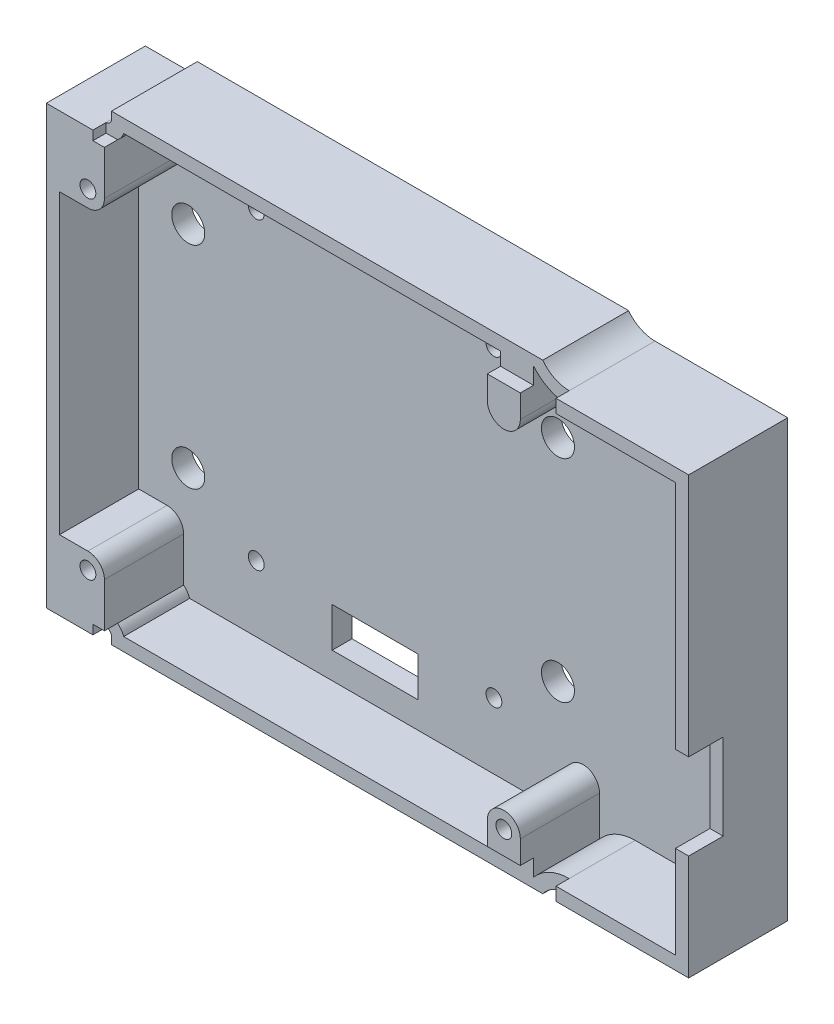
SolidWorks part; units mm, degrees
ref_plane "Ebene vorne" through (0, 0, 0) normal (0, 0, 1) x (1, 0, 0)
ref_plane "Ebene oben" through (0, 0, 0) normal (0, 1, 0) x (1, 0, 0)
ref_plane "Ebene rechts" through (0, 0, 0) normal (1, 0, 0) x (0, 0, -1)
sketch "Skizze1" plane through (0, 0, 0) normal (0, 0, 1) x (1, 0, 0)
  line L0 (-40.78, 38.7) -> (-40.78, 33.92)
  line L1 (-41.59, 33.11) -> (-48.65, 33.11)
  line L2 (-48.65, 33.11) -> (-48.65, -33.11)
  line L3 (-48.65, -33.11) -> (-41.59, -33.11)
  line L4 (-40.78, -33.92) -> (-40.78, -38.7)
  line L5 (-40.78, -38.7) -> (-39.35, -38.7)
  line L6 (-39.35, -38.7) -> (-39.35, 38.7)
  line L7 (-39.35, 38.7) -> (-40.78, 38.7)
  line L8 (48.65, 3) -> (45.65, 3)
  line L9 (45.65, 3) -> (45.65, -30)
  line L10 (45.65, -30) -> (34.2, -30)
  line L11 (34.2, -33) -> (48.65, -33)
  line L12 (48.65, -33) -> (48.65, 3)
  line L13 (45.65, 18) -> (48.65, 18)
  line L14 (48.65, 18) -> (48.65, 33)
  line L15 (48.65, 33) -> (34.2, 33)
  line L16 (34.2, 30) -> (45.65, 30)
  line L17 (45.65, 30) -> (45.65, 18)
  line L18 (34.2, 33) -> (28.5521, 33)
  line L19 (23.85, 36.3) -> (5.65, 36.3)
  line L20 (2.287, 35) -> (-20.522, 35)
  line L21 (-25.35, 38.7) -> (-27.35, 38.7)
  line L22 (-27.35, 38.7) -> (-27.35, -38.7)
  line L23 (-27.35, -38.7) -> (-25.35, -38.7)
  line L24 (-20.522, -35) -> (2.287, -35)
  line L25 (5.65, -36.3) -> (23.85, -36.3)
  line L26 (28.5521, -33) -> (34.2, -33)
  line L27 (34.2, -30) -> (23.85, -30)
  line L28 (23.85, -30) -> (23.85, -24)
  line L29 (23.85, -24) -> (17.45, -24)
  line L30 (17.45, -24) -> (17.45, -33.3)
  line L31 (17.45, -33.3) -> (9.3559, -33.3)
  line L32 (7.65, -33) -> (-24.35, -33)
  line L33 (-24.35, -33) -> (-24.35, 33)
  line L34 (-24.35, 33) -> (7.65, 33)
  line L35 (9.3559, 33.3) -> (17.45, 33.3)
  line L36 (17.45, 33.3) -> (17.45, 24)
  line L37 (17.45, 24) -> (23.85, 24)
  line L38 (23.85, 24) -> (23.85, 30)
  line L39 (23.85, 30) -> (34.2, 30)
  line L40 (-39.35, -38.7) -> (-27.35, -38.7)
  line L41 (-39.35, 38.7) -> (-27.35, 38.7)
  line L42 (48.65, 18) -> (48.65, 3)
  arc A0 (-41.59, 33.11) -> (-40.78, 33.92) centre (-41.59, 33.92) ccw
  arc A1 (-40.78, -33.92) -> (-41.59, -33.11) centre (-41.59, -33.92) ccw
  arc A2 (23.85, 36.3) -> (28.5521, 33) centre (28.5521, 38) ccw
  arc A3 (2.287, 35) -> (5.65, 36.3) centre (2.287, 40) ccw
  arc A4 (-25.35, 38.7) -> (-20.522, 35) centre (-20.522, 40) ccw
  arc A5 (-20.522, -35) -> (-25.35, -38.7) centre (-20.522, -40) ccw
  arc A6 (5.65, -36.3) -> (2.287, -35) centre (2.287, -40) ccw
  arc A7 (28.5521, -33) -> (23.85, -36.3) centre (28.5521, -38) ccw
  arc A8 (7.65, -33) -> (9.3559, -33.3) centre (9.3559, -28.3) ccw
  arc A9 (9.3559, 33.3) -> (7.65, 33) centre (9.3559, 28.3) ccw
extrude "Aufsatz-Linear austragen1" add sketch "Skizze1" along normal blind 15 contours A1 L4 L5 L6 L7 L0 A0 L1 L2 L3 | L41 L6 L40 L22 | A9 L35 L36 L37 L38 L39 L16 L17 L13 L14 L15 L18 A2 L19 A3 L20 A4 L21 L22 L23 A5 L24 A6 L25 A7 L26 L11 L12 L8 L9 L10 L27 L28 L29 L30 L31 A8 L32 L33 L34 | L35 A9 L34 L33 L32 A8 L31 L30 L29 L28 L27 L10 L9 L8 L42 L13 L17 L16 L39 L38 L37 L36
sketch "Skizze2" plane through (0, 0, 15) normal (0, 0, 1) x (1, 0, 0)
  line L56 (46.65, -31) -> (46.65, 31)
  line L57 (46.65, 31) -> (28.5521, 31)
  line L58 (22.6099, 34.3) -> (6.3502, 34.3)
  line L59 (2.287, 33) -> (-20.522, 33)
  line L60 (-26.6953, 36.7) -> (-38.78, 36.7)
  line L61 (-38.78, 36.7) -> (-38.78, 33.92)
  line L62 (-41.59, 31.11) -> (-46.65, 31.11)
  line L63 (-46.65, 31.11) -> (-46.65, -31.11)
  line L64 (-46.65, -31.11) -> (-41.59, -31.11)
  line L65 (-38.78, -33.92) -> (-38.78, -36.7)
  line L66 (-38.78, -36.7) -> (-26.6953, -36.7)
  line L67 (-20.522, -33) -> (2.287, -33)
  line L68 (6.3502, -34.3) -> (22.6099, -34.3)
  line L69 (28.5521, -31) -> (46.65, -31)
  line L70 (46.65, -31) -> (46.65, 31)
  line L71 (46.65, 31) -> (28.5521, 31)
  line L72 (22.6099, 34.3) -> (6.3502, 34.3)
  line L73 (2.287, 33) -> (-20.522, 33)
  line L74 (-26.6953, 36.7) -> (-38.78, 36.7)
  line L75 (-38.78, 36.7) -> (-38.78, 33.92)
  line L76 (-41.59, 31.11) -> (-46.65, 31.11)
  line L77 (-46.65, 31.11) -> (-46.65, -31.11)
  line L78 (-46.65, -31.11) -> (-41.59, -31.11)
  line L79 (-38.78, -33.92) -> (-38.78, -36.7)
  line L80 (-38.78, -36.7) -> (-26.6953, -36.7)
  line L81 (-20.522, -33) -> (2.287, -33)
  line L82 (6.3502, -34.3) -> (22.6099, -34.3)
  line L83 (28.5521, -31) -> (46.65, -31)
  arc A32 (22.6099, 34.3) -> (28.5521, 31) centre (28.5521, 38) ccw
  arc A33 (2.287, 33) -> (6.3502, 34.3) centre (2.287, 40) ccw
  arc A34 (-26.6953, 36.7) -> (-20.522, 33) centre (-20.522, 40) ccw
  arc A35 (-41.59, 31.11) -> (-38.78, 33.92) centre (-41.59, 33.92) ccw
  arc A36 (-38.78, -33.92) -> (-41.59, -31.11) centre (-41.59, -33.92) ccw
  arc A37 (-20.522, -33) -> (-26.6953, -36.7) centre (-20.522, -40) ccw
  arc A38 (6.3502, -34.3) -> (2.287, -33) centre (2.287, -40) ccw
  arc A39 (28.5521, -31) -> (22.6099, -34.3) centre (28.5521, -38) ccw
  arc A40 (22.6099, 34.3) -> (28.5521, 31) centre (28.5521, 38) ccw
  arc A41 (2.287, 33) -> (6.3502, 34.3) centre (2.287, 40) ccw
  arc A42 (-26.6953, 36.7) -> (-20.522, 33) centre (-20.522, 40) ccw
  arc A43 (-41.59, 31.11) -> (-38.78, 33.92) centre (-41.59, 33.92) ccw
  arc A44 (-38.78, -33.92) -> (-41.59, -31.11) centre (-41.59, -33.92) ccw
  arc A45 (-20.522, -33) -> (-26.6953, -36.7) centre (-20.522, -40) ccw
  arc A46 (6.3502, -34.3) -> (2.287, -33) centre (2.287, -40) ccw
  arc A47 (28.5521, -31) -> (22.6099, -34.3) centre (28.5521, -38) ccw
  dimension "D1" = 2
extrude "Schnitt-Linear austragen1" cut sketch "Skizze2" against normal blind 12
sketch "Skizze3" plane through (0, 0, 3) normal (0, 0, 1) x (1, 0, 0)
  line L0 (-48.65, 0) -> (48.65, 0) construction
  line L1 (-48.65, 0) -> (48.65, 0) construction
  line L2 (48.65, -33) -> (48.65, 33) construction
  line L3 (-48.65, 33.11) -> (-48.65, -33.11) construction
  circle A5 centre (-42.35, 25) radius 1.2
  circle A6 centre (20.65, 27.5) radius 1.2
  circle A7 centre (20.65, -27.5) radius 1.2
  circle A8 centre (-42.35, -25) radius 1.2
  dimension "D1" = 2.4
  dimension "D2" = 2.4
extrude "Schnitt-Linear austragen2" cut sketch "Skizze3" against normal blind 10
sketch "Skizze4" plane through (48.65, 0, 0) normal (1, 0, 0) x (0, 0, -1)
  line L0 (-15, -33) -> (-15, 33) construction
  line L1 (-15, -4) -> (-9.78, -4)
  line L2 (-15, -4) -> (-15, -17)
  line L3 (-15, -17) -> (-9.78, -17)
  line L4 (-9.78, -4) -> (-9.78, -17)
  line L5 (-15, -4) -> (-19.215, -4) construction
  point P8 (0, 0)
  point P9 (-12.39, -17)
  dimension "D1" = 5.22
  dimension "D2" = 13
extrude "Schnitt-Linear austragen3" cut sketch "Skizze4" against normal blind 5
sketch "Skizze5" plane through (0, 0, 0) normal (0, 0, -1) x (-1, 0, 0)
  circle A4 centre (-7.15, 23) radius 1.2
  circle A5 centre (28.85, 23) radius 1.2
  circle A6 centre (-7.15, -23) radius 1.2
  circle A7 centre (28.85, -23) radius 1.2
extrude "Schnitt-Linear austragen4" cut sketch "Skizze5" against normal through all both
sketch "Skizze6" plane through (0, 0, 0) normal (0, 0, -1) x (-1, 0, 0)
  line L0 (11.15, -17.75) -> (11.15, 17.75) construction
  line L1 (-21.35, -17.75) -> (43.65, -17.75) construction
  line L2 (43.65, 17.75) -> (-21.35, 17.75) construction
  line L3 (48.65, 0) -> (-26.35, 0) construction
  line L4 (48.65, 33.11) -> (48.65, -33.11) construction
  line L5 (-26.35, -10) -> (-26.35, 10) construction
  circle A0 centre (-16.85, -16) radius 2.5
  circle A1 centre (-16.85, 16) radius 2.5
  circle A2 centre (39.15, 16) radius 2.5
  circle A3 centre (39.15, -16) radius 2.5
  dimension "D1" = 5
  dimension "D2" = 28
  dimension "D3" = 16
extrude "Schnitt-Linear austragen5" cut sketch "Skizze6" against normal through all both
sketch "Skizze7" plane through (0, 0, 0) normal (0, 0, -1) x (-1, 0, 0)
  line L1 (17.35, -29) -> (4.35, -29)
  line L2 (17.35, -29) -> (17.35, -23)
  line L3 (17.35, -23) -> (4.35, -23)
  line L4 (4.35, -29) -> (4.35, -23)
  line L5 (17.35, 23) -> (4.35, 23)
  line L6 (17.35, 23) -> (17.35, 29)
  line L7 (17.35, 29) -> (4.35, 29)
  line L8 (4.35, 23) -> (4.35, 29)
extrude "Schnitt-Linear austragen6" cut sketch "Skizze7" against normal through all both
sketch "Skizze8" plane through (0, 0, 3) normal (0, 0, 1) x (1, 0, 0)
  line L0 (-48.65, 0) -> (48.65, 0) construction
  line L1 (-48.65, 33.11) -> (-48.65, -33.11) construction
  line L2 (48.65, -4) -> (48.65, 33) construction
  line L3 (0, 0) -> (0, 35) construction
  line L4 (2.287, 35) -> (-20.522, 35) construction
  circle A0 centre (-42.35, 25) radius 2.5
  circle A1 centre (-42.35, 25) radius 1.2
  circle A2 centre (-42.35, -25) radius 1.2
  circle A3 centre (-42.35, -25) radius 2.5
  circle A4 centre (20.65, 27.5) radius 2.5
  circle A5 centre (20.65, 27.5) radius 1.2
  circle A6 centre (20.65, -27.5) radius 1.2
  circle A7 centre (20.65, -27.5) radius 2.5
  dimension "D1" = 5
  dimension "D2" = 5
extrude "Aufsatz-Linear austragen2" add sketch "Skizze8" along normal up to surface (12 mm away) up to face at (-5.0444, -0.875, 15)
sketch "Skizze9" plane through (0, 0, 3) normal (0, 0, 1) x (1, 0, 0)
  line L0 (-39.85, 25) -> (-39.85, 31.933)
  line L1 (-39.85, 31.933) -> (-46.65, 31.933)
  line L2 (-46.65, 31.933) -> (-46.65, 22.5)
  line L3 (-46.65, 31.11) -> (-46.65, -31.11) construction
  line L4 (-46.65, 22.5) -> (-42.35, 22.5)
  line L5 (-48.65, 0) -> (46.65, 0) construction
  line L6 (-48.65, 33.11) -> (-48.65, -33.11) construction
  line L7 (46.65, -31) -> (46.65, 31) construction
  line L9 (18.15, 33) -> (18.15, 27.5)
  line L17 (-46.65, -22.5) -> (-42.35, -22.5)
  line L18 (-46.65, -31.933) -> (-46.65, -22.5)
  line L19 (-39.85, -31.933) -> (-46.65, -31.933)
  line L20 (-39.85, -25) -> (-39.85, -31.933)
  line L21 (-20.522, -33) -> (-38.9349, -33)
  line L22 (-20.522, -35) -> (-38.78, -35)
  line L23 (-38.78, -33.92) -> (-38.78, -36.7) construction
  line L24 (-38.78, -35) -> (-38.9349, -33)
  line L25 (-20.522, -33) -> (-20.522, -35)
  line L26 (-20.522, 33) -> (-20.522, 35)
  line L27 (-38.78, 35) -> (-38.9349, 33)
  line L28 (-20.522, 35) -> (-38.78, 35)
  line L29 (-20.522, 33) -> (-38.9349, 33)
  line L30 (2.287, 33) -> (18.15, 33)
  line L31 (2.287, 35) -> (24.5521, 35)
  line L32 (24.5521, 35) -> (24.5521, 34.3)
  line L33 (23.15, 34.3) -> (24.5521, 34.3)
  line L34 (2.287, 35) -> (2.287, 33)
  line L35 (2.287, -35) -> (2.287, -33)
  line L36 (23.15, -34.3) -> (24.5521, -34.3)
  line L37 (24.5521, -35) -> (24.5521, -34.3)
  line L38 (2.287, -35) -> (24.5521, -35)
  line L39 (2.287, -33) -> (18.15, -33)
  line L40 (23.15, -27.5) -> (23.15, -34.3)
  line L41 (18.15, -27.5) -> (18.15, -33)
  line L42 (23.15, 34.3) -> (23.15, 27.5)
  circle A0 centre (20.65, 27.5) radius 2.5 construction
  circle A1 centre (20.65, 27.5) radius 2.5 construction
  arc A2 (-39.85, 25) -> (-42.35, 22.5) centre (-42.35, 25) cw
  circle A3 centre (-42.35, 25) radius 1.2
  arc A6 (18.15, 27.5) -> (23.15, 27.5) centre (20.65, 27.5) ccw
  circle A11 centre (-42.35, -25) radius 1.2
  arc A12 (-39.85, -25) -> (-42.35, -22.5) centre (-42.35, -25) ccw
  arc A13 (-38.78, -33.92) -> (-41.59, -31.11) centre (-41.59, -33.92) ccw construction
  arc A14 (23.85, 36.3) -> (28.5521, 33) centre (28.5521, 38) ccw construction
  circle A15 centre (20.65, -27.5) radius 1.2
  arc A16 (23.15, -27.5) -> (18.15, -27.5) centre (20.65, -27.5) ccw
extrude "Aufsatz-Linear austragen3" add sketch "Skizze9" along normal up to surface (12 mm away) up to face at (-5.0444, -0.875, 15)
sketch "Skizze10" plane through (0, 0, 15) normal (0, 0, 1) x (1, 0, 0)
  line L0 (-40.78, 38.7) -> (-40.78, 33.92) construction
  line L1 (-40.78, 35) -> (36.193, 35)
  line L2 (-40.78, 35) -> (-40.78, 40.1609)
  line L3 (-40.78, 40.1609) -> (36.193, 40.1609)
  line L4 (36.193, 35) -> (36.193, 40.1609)
  line L5 (-48.65, 0) -> (46.65, 0) construction
  line L6 (-48.65, 33.11) -> (-48.65, -33.11) construction
  line L7 (46.65, -31) -> (46.65, 31) construction
  line L8 (36.193, -35) -> (36.193, -40.1609)
  line L9 (-40.78, -40.1609) -> (36.193, -40.1609)
  line L10 (-40.78, -35) -> (-40.78, -40.1609)
  line L11 (-40.78, -35) -> (36.193, -35)
extrude "Schnitt-Linear austragen7" cut sketch "Skizze10" against normal through all both and the other way through all
sketch "Skizze11" plane through (0, 0, 15) normal (0, 0, 1) x (1, 0, 0)
  line L19 (-48.65, 0) -> (0, 0) construction
  line L20 (-48.65, 33.11) -> (-48.65, -33.11) construction
  line L33 (-41.59, 31.7135) -> (-41.59, 35)
  line L34 (-41.59, 35) -> (28.5521, 35)
  line L35 (28.5521, 35) -> (28.5521, 31)
  line L36 (28.5521, 31) -> (18.15, 31)
  line L37 (18.15, 33) -> (18.15, 27.5) construction
  line L38 (18.15, 31) -> (18.15, 33)
  line L39 (18.15, 33) -> (-38.9349, 33)
  line L40 (-38.9349, 33) -> (-38.9349, 31.7135)
  line L41 (-38.9349, 31.7135) -> (-41.59, 31.7135)
  line L42 (-38.9349, -33) -> (-38.9349, -31.7135)
  line L43 (18.15, -33) -> (-38.9349, -33)
  line L44 (18.15, -31) -> (18.15, -33)
  line L45 (28.5521, -31) -> (18.15, -31)
  line L46 (28.5521, -35) -> (28.5521, -31)
  line L47 (-41.59, -35) -> (28.5521, -35)
  line L48 (-41.59, -31.7135) -> (-41.59, -35)
  line L49 (-38.9349, -31.7135) -> (-41.59, -31.7135)
extrude "Schnitt-Linear austragen8" cut sketch "Skizze11" against normal blind 2
